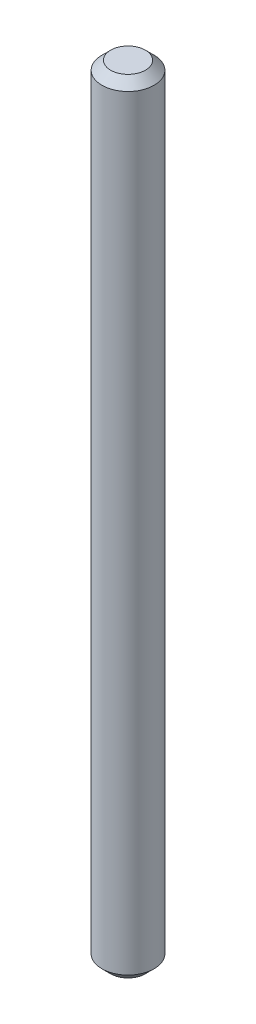
SolidWorks part; units mm, degrees
ref_plane "Front Plane" through (0, 0, 0) normal (0, 0, 1) x (1, 0, 0)
ref_plane "Top Plane" through (0, 0, 0) normal (0, 1, 0) x (1, 0, 0)
ref_plane "Right Plane" through (0, 0, 0) normal (1, 0, 0) x (0, 0, -1)
sketch "Sketch1" plane through (0, 0, 0) normal (0, 1, 0) x (1, 0, 0)
  circle A0 centre (0, 0) radius 3
  dimension "D1" = 6
extrude "Boss-Extrude1" add sketch "Sketch1" along normal blind 90
chamfer "Chamfer1" distance 1 angle 45 2 edges at (0, 0, 3) (0, 90, 3)
